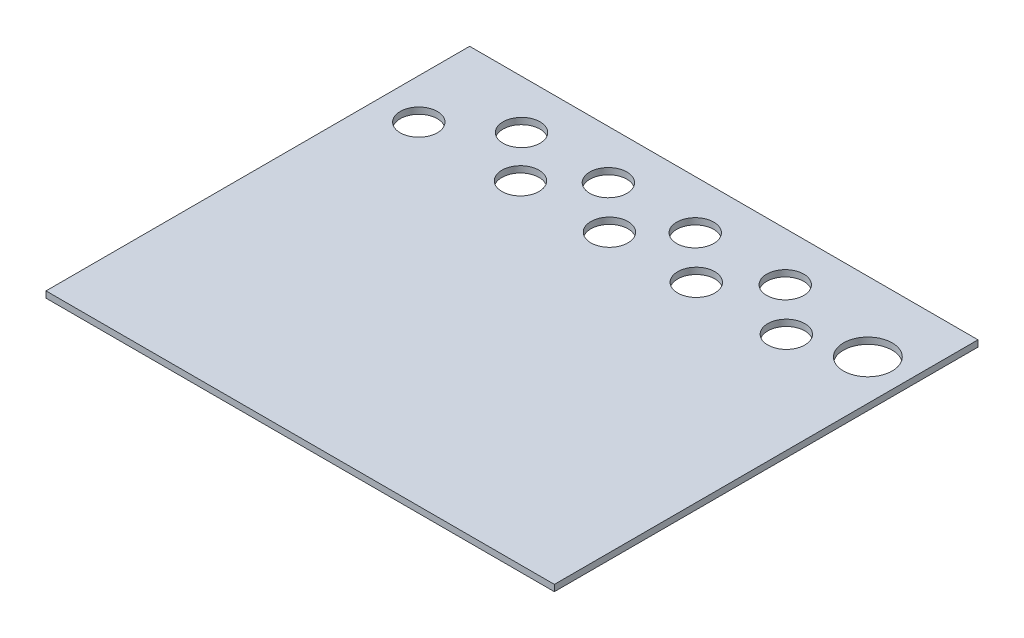
SolidWorks part; units mm, degrees
ref_plane "Front Plane" through (0, 0, 0) normal (0, 0, 1) x (1, 0, 0)
ref_plane "Top Plane" through (0, 0, 0) normal (0, 1, 0) x (1, 0, 0)
ref_plane "Right Plane" through (0, 0, 0) normal (1, 0, 0) x (0, 0, -1)
sketch "Sketch1" plane through (0, 0, 0) normal (0, 1, 0) x (1, 0, 0)
  line L0 (0, 0) -> (240, 0) construction
  line L1 (0, 0) -> (0, 200) construction
  line L2 (118.2981, 356.5704) -> (618.222, 365.2966) construction
  line L4 (0, 0) -> (240, 0)
  line L5 (0, 0) -> (0, 200)
  line L6 (0, 200) -> (240, 200)
  line L7 (240, 0) -> (240, 200)
  dimension "D1" = 200
  dimension "D2" = 240
  dimension "D3" = 240
  dimension "D4" = 200
extrude "Boss-Extrude1" add sketch "Sketch1" along normal blind 3
hole_wizard "M16 Clearance Hole1" positions "Sketch4" profile "Sketch3" hole size "M16" standard "ANSI Metric" end condition through all
sketch "Sketch4" plane through (0, 3, 0) normal (0, 1, 0) x (1, 0, 0)
  line L0 (0, 200) -> (0, 0) construction
  line L1 (240, 200) -> (0, 200) construction
  point P0 (19, 157)
  point P2 (47.5, 177)
  point P4 (67, 157)
  point P6 (88.5, 177)
  point P8 (109, 157)
  point P10 (129.5, 177)
  point P12 (150, 157)
  point P14 (172, 177)
  point P16 (192.5, 157)
  dimension "D1" = 19
  dimension "D2" = 43
  dimension "D3" = 43
  dimension "D4" = 43
  dimension "D5" = 43
  dimension "D6" = 43
  dimension "D7" = 23
  dimension "D8" = 23
  dimension "D9" = 23
  dimension "D10" = 23
  dimension "D11" = 47.5
  dimension "D12" = 67
  dimension "D13" = 88.5
  dimension "D14" = 109
  dimension "D15" = 129.5
  dimension "D16" = 150
  dimension "D17" = 172
  dimension "D18" = 192.5
sketch "Sketch3" plane through (19, 3, -157) normal (1, 0, 0) x (0, 0, 1)
  line L0 (0, 0) -> (0, 3)
  line L1 (0, 3) -> (8.75, 3)
  line L2 (8.75, 3) -> (8.75, 0)
  line L5 (8.75, 0) -> (0, 0)
  line L11 (0, -6.35) -> (0, 107.95) construction
  dimension "Thru Hole Dia." = 17.5
  dimension "Thru Hole Depth" = 3
hole_wizard "M22 Clearance Hole1" positions "Sketch5" profile "Sketch6" hole size "M22" standard "ANSI Metric" end condition through all
sketch "Sketch5" plane through (0, 3, 0) normal (0, 1, 0) x (1, 0, 0)
  line L0 (240, 0) -> (240, 200) construction
  line L1 (240, 200) -> (0, 200) construction
  point P0 (221, 167)
  dimension "D1" = 19
  dimension "D2" = 33
sketch "Sketch6" plane through (221, 3, -167) normal (1, 0, 0) x (0, 0, 1)
  line L0 (0, 0) -> (0, 3)
  line L1 (0, 3) -> (11.5, 3)
  line L2 (11.5, 3) -> (11.5, 0)
  line L5 (11.5, 0) -> (0, 0)
  line L11 (0, -6.35) -> (0, 107.95) construction
  dimension "Thru Hole Dia." = 23
  dimension "Thru Hole Depth" = 3
